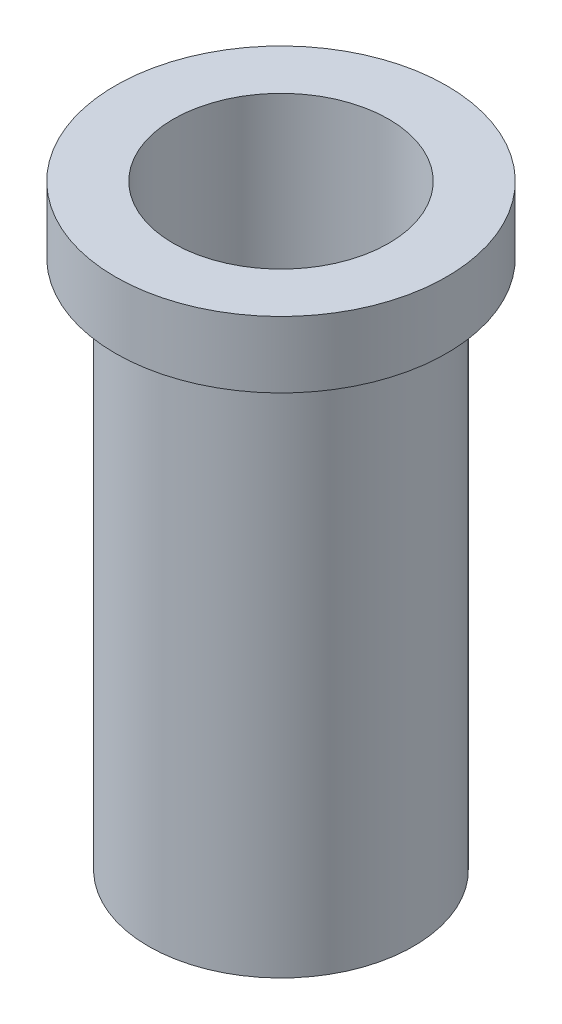
SolidWorks part; units mm, degrees
ref_plane "Ebene vorne" through (0, 0, 0) normal (0, 0, 1) x (1, 0, 0)
ref_plane "Ebene oben" through (0, 0, 0) normal (0, 1, 0) x (1, 0, 0)
ref_plane "Ebene rechts" through (0, 0, 0) normal (1, 0, 0) x (0, 0, -1)
sketch "Skizze1" plane through (0, 0, 0) normal (0, 1, 0) x (1, 0, 0)
  circle A0 centre (0, 0) radius 5
  dimension "D1" = 10
extrude "Aufsatz-Linear austragen1" add sketch "Skizze1" along normal blind 2
sketch "Skizze2" plane through (0, 0, 0) normal (0, -1, 0) x (1, 0, 0)
  circle A0 centre (0, 0) radius 4
  dimension "D1" = 8
extrude "Aufsatz-Linear austragen2" add sketch "Skizze2" along normal blind 16
sketch "Skizze3" plane through (0, 2, 0) normal (0, 1, 0) x (1, 0, 0)
  circle A0 centre (0, 0) radius 3.25
  dimension "D1" = 6.5
extrude "Schnitt-Linear austragen1" cut sketch "Skizze3" against normal offset from surface (16 mm away) 2 up to face at (0, -16, -4)
sketch "Skizze4" plane through (0, -16, 0) normal (0, -1, 0) x (1, 0, 0)
  circle A0 centre (0, 0) radius 1.5
  dimension "D1" = 3
extrude "Schnitt-Linear austragen2" cut sketch "Skizze4" against normal up to surface (2 mm away) up to face at (0, -14, -3.25)
